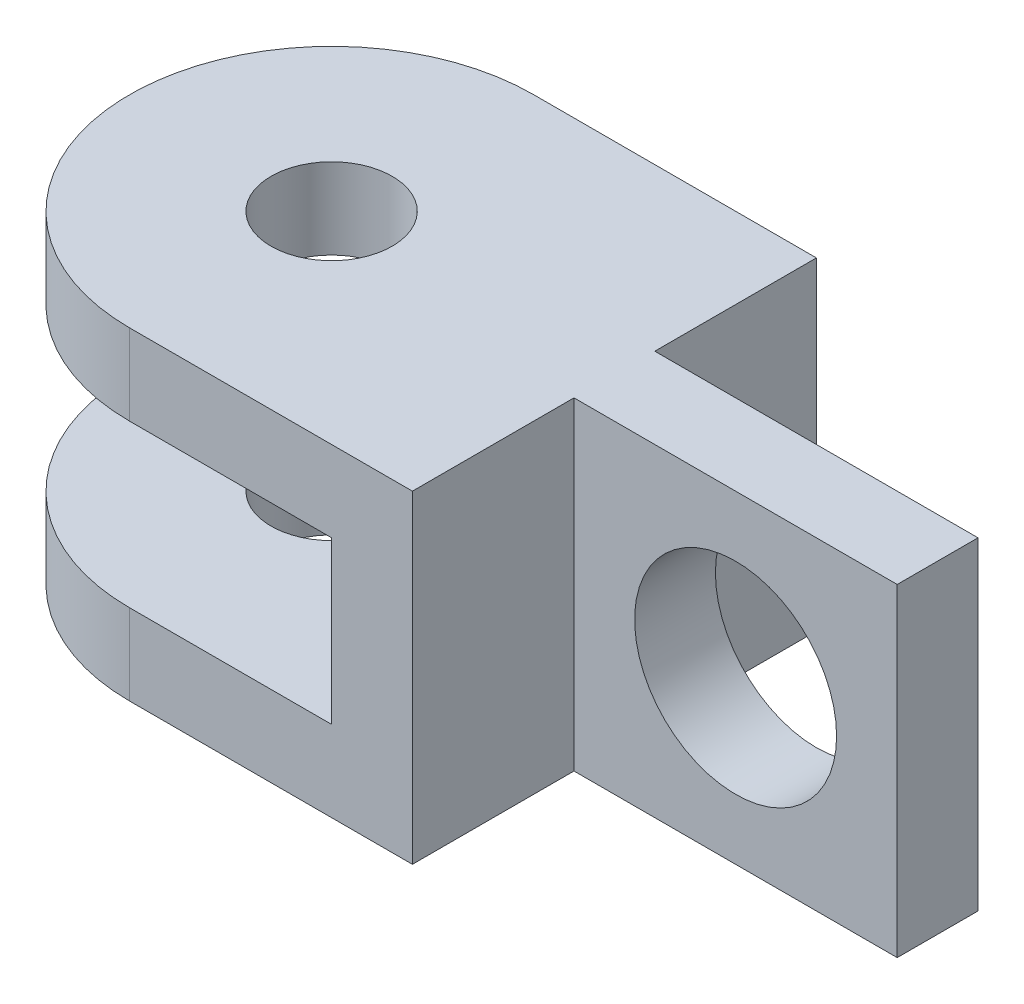
SolidWorks part; units mm, degrees
ref_plane "前视基准面" through (0, 0, 0) normal (0, 0, 1) x (1, 0, 0)
ref_plane "上视基准面" through (0, 0, 0) normal (0, 1, 0) x (1, 0, 0)
ref_plane "右视基准面" through (0, 0, 0) normal (1, 0, 0) x (0, 0, -1)
other "Configuration Table"
sketch "草图1" plane through (0, 0, 0) normal (0, 1, 0) x (1, 0, 0)
  line L1 (50, 0) -> (200, 0)
  line L3 (50, -100) -> (200, -100)
  line L4 (200, 0) -> (200, -100)
  arc A0 (50, 0) -> (50, -100) centre (50, -50) ccw
  circle A1 centre (50, -50) radius 15
  dimension "D5" = 100
  dimension "D2" = 50
  dimension "D6" = 30
  dimension "D1" = 100
  dimension "D3" = 150
  dimension "D4" = 0
  dimension "D7" = 50
extrude "凸台-拉伸1" add sketch "草图1" along normal blind 80
sketch "草图5" plane through (0, 0, 100) normal (0, 0, 1) x (1, 0, 0)
  line L0 (50, 80) -> (200, 80) construction
  line L1 (200, 80) -> (200, 0) construction
  line L2 (50, 80) -> (50, 0) construction
  line L3 (-100, 60) -> (100, 60)
  line L4 (-100, 60) -> (-100, 20)
  line L5 (-100, 20) -> (100, 20)
  line L6 (100, 60) -> (100, 20)
  circle A0 centre (160, 40) radius 25
  dimension "D3" = 50
  dimension "D1" = 40
  dimension "D2" = 40
  dimension "D4" = 40
  dimension "D5" = 20
  dimension "D6" = 200
  dimension "D7" = 50
extrude "切除-拉伸5" cut sketch "草图5" against normal blind 100
sketch "草图6" plane through (0, 0, 100) normal (0, 0, 1) x (1, 0, 0)
  line L0 (100, 20) -> (100, 60) construction
  line L1 (120, 90) -> (220, 90)
  line L2 (120, 90) -> (120, -10)
  line L3 (120, -10) -> (220, -10)
  line L4 (220, 90) -> (220, -10)
  line L5 (50, 80) -> (200, 80) construction
  dimension "D1" = 20
  dimension "D2" = 100
  dimension "D3" = 10
  dimension "D4" = 100
extrude "切除-拉伸7" cut sketch "草图6" against normal blind 40
sketch "草图8" plane through (0, 0, 0) normal (0, 0, -1) x (-1, 0, 0)
  line L0 (-100, 20) -> (-100, 60) construction
  line L1 (-220, 90) -> (-120, 90)
  line L2 (-220, 90) -> (-220, -10)
  line L3 (-220, -10) -> (-120, -10)
  line L4 (-120, 90) -> (-120, -10)
  line L5 (-200, 80) -> (-50, 80) construction
  dimension "D1" = 100
  dimension "D2" = 100
  dimension "D3" = 20
  dimension "D4" = 10
extrude "切除-拉伸8" cut sketch "草图8" against normal blind 40
